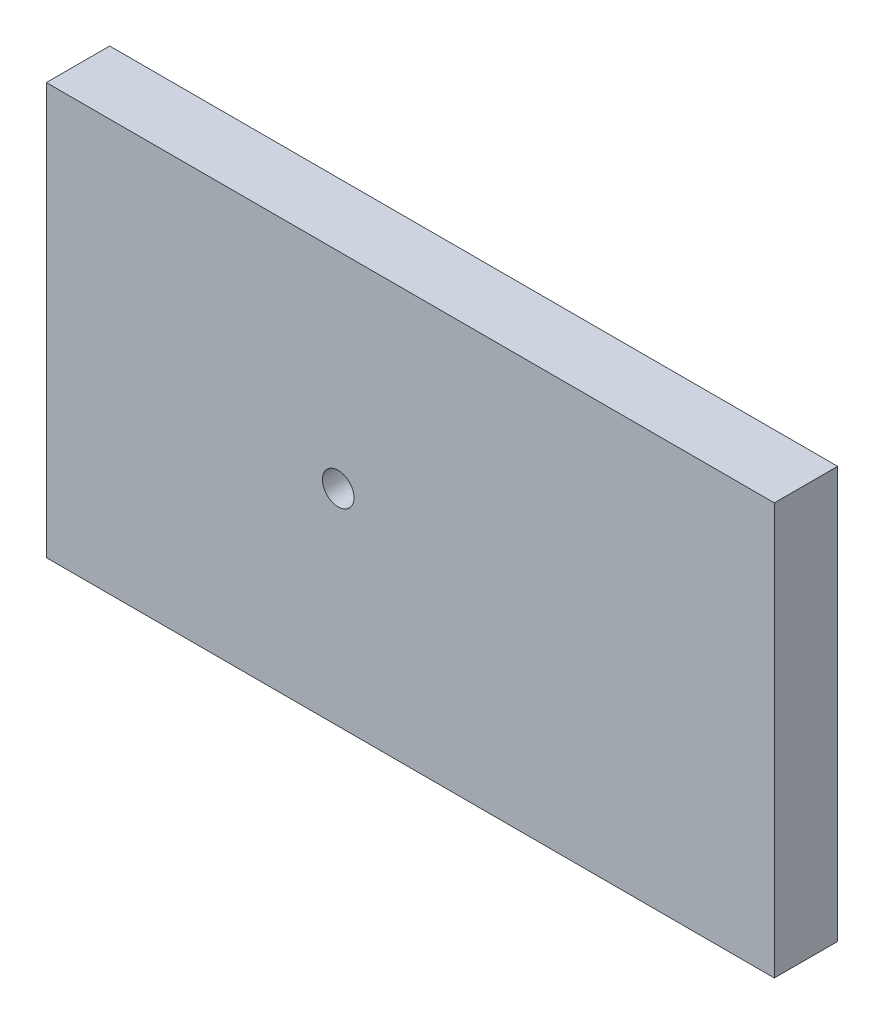
SolidWorks part; units mm, degrees
ref_plane "Plan de face" through (0, 0, 0) normal (0, 0, 1) x (1, 0, 0)
ref_plane "Plan de dessus" through (0, 0, 0) normal (0, 1, 0) x (1, 0, 0)
ref_plane "Plan de droite" through (0, 0, 0) normal (1, 0, 0) x (0, 0, -1)
sketch "Esquisse1" plane through (0, 0, 0) normal (0, 0, 1) x (1, 0, 0)
  line L0 (0, 0) -> (-73.025, 0) construction
  line L1 (-73.025, 41.275) -> (73.025, 41.275)
  line L2 (-73.025, 41.275) -> (-73.025, -41.275)
  line L3 (-73.025, -41.275) -> (73.025, -41.275)
  line L4 (73.025, 41.275) -> (73.025, -41.275)
  line L5 (-73.025, 41.275) -> (73.025, -41.275) construction
  line L6 (-73.025, -41.275) -> (73.025, 41.275) construction
  line L7 (-14.475, 41.275) -> (-14.475, -41.275) construction
  circle A0 centre (-14.475, 0) radius 3.175
  point P0 (0, 0)
  dimension "D4" = 6.35
  dimension "D1" = 82.55
  dimension "D2" = 146.05
  dimension "D3" = 87.5
extrude "Boss.-Extru.1" add sketch "Esquisse1" along normal blind 12.7
